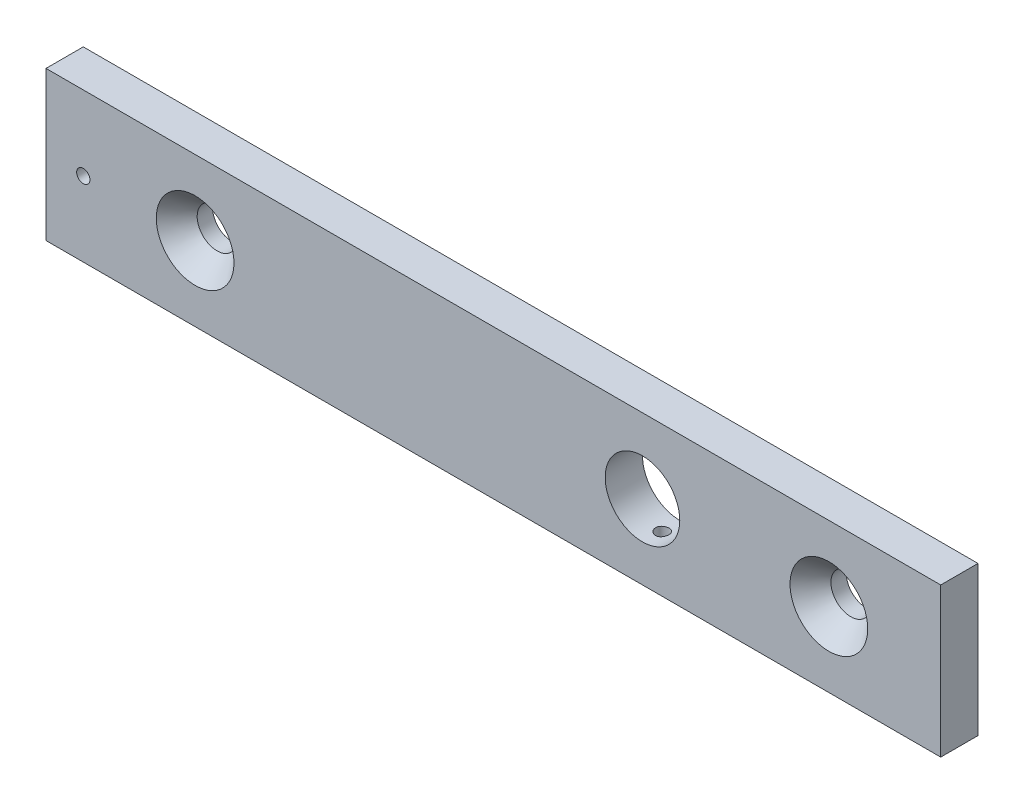
SolidWorks part; units mm, degrees
material "Brass"
ref_plane "Front Plane" through (0, 0, 0) normal (0, 0, 1) x (1, 0, 0)
ref_plane "Top Plane" through (0, 0, 0) normal (0, 1, 0) x (1, 0, 0)
ref_plane "Right Plane" through (0, 0, 0) normal (1, 0, 0) x (0, 0, -1)
sketch "Sketch1" plane through (0, 0, 0) normal (0, 0, 1) x (1, 0, 0)
  line L0 (-76.2, 12.7) -> (76.2, -12.7) construction
  line L1 (-76.2, 12.7) -> (76.2, 12.7)
  line L2 (-76.2, 12.7) -> (-76.2, -12.7)
  line L3 (-76.2, -12.7) -> (76.2, -12.7)
  line L4 (76.2, 12.7) -> (76.2, -12.7)
  dimension "D1" = 152.4
  dimension "D2" = 25.4
extrude "Extrude1" add sketch "Sketch1" along normal blind 6.35
hole_wizard "#4-40 Tapped Hole2" positions "3DSketch2" profile "Sketch10" tap size "#4-40" standard "Ansi Inch"
sketch3d "3DSketch2"
  line L0 (-76.2, 12.7, 6.35) -> (-76.2, -12.7, 6.35) construction
  line L1 (-76.2, -12.7, 6.35) -> (76.2, -12.7, 6.35) construction
  point P0 (-69.85, 0, 6.35)
  dimension "D1" = 6.35
  dimension "D2" = 12.7
sketch "Sketch10" plane through (-69.85, 0, 6.35) normal (1, 0, 0) x (0, -1, 0)
  line L0 (0, 0) -> (0, 3.9812)
  line L1 (0, 3.9812) -> (1.1303, 3.302)
  line L2 (1.1303, 3.302) -> (1.1303, 0)
  line L5 (1.1303, 0) -> (0, 0)
  line L10 (0, 3.9812) -> (-1.1303, 3.302) construction
  line L11 (0, -6.35) -> (0, 107.95) construction
  dimension "Tap Drill Dia." = 2.2606
  dimension "Tap Drill Depth" = 3.302
  dimension "Drill Angle" = 118
cosmetic thread "Hole Thread3" parameters "D1"=3.302, "D2"=2.8448
hole_wizard "1/2 (0.5) Diameter Hole1" positions "3DSketch3" profile "Sketch13" hole size "1/2" standard "Ansi Inch" end condition through all
sketch3d "3DSketch3"
  line L0 (76.2, 12.7, 6.35) -> (-76.2, 12.7, 6.35) construction
  line L1 (-76.2, 12.7, 6.35) -> (-76.2, -12.7, 6.35) construction
  point P0 (25.4, 0, 6.35)
  dimension "D1" = 12.7
  dimension "D2" = 101.6
sketch "Sketch13" plane through (25.4, 0, 6.35) normal (1, 0, 0) x (0, -1, 0)
  line L0 (0, 0) -> (0, 6.35)
  line L1 (0, 6.35) -> (6.35, 6.35)
  line L2 (6.35, 6.35) -> (6.35, 0)
  line L5 (6.35, 0) -> (0, 0)
  line L11 (0, -6.35) -> (0, 107.95) construction
  dimension "Thru Hole Dia." = 12.7
  dimension "Thru Hole Depth" = 6.35
hole_wizard "#4-40 Tapped Hole3" positions "3DSketch4" profile "Sketch14" tap size "#4-40" standard "Ansi Inch"
sketch3d "3DSketch4"
  point P0 (25.6107, -12.7, 3.1789)
sketch "Sketch14" plane through (25.6107, -12.7, 3.1789) normal (1, 0, 0) x (0, 0, -1)
  line L0 (0, 0) -> (0, 9.5692)
  line L1 (0, 9.5692) -> (1.1303, 8.89)
  line L2 (1.1303, 8.89) -> (1.1303, 0)
  line L5 (1.1303, 0) -> (0, 0)
  line L10 (0, 9.5692) -> (-1.1303, 8.89) construction
  line L11 (0, -6.35) -> (0, 107.95) construction
  dimension "Tap Drill Dia." = 2.2606
  dimension "Tap Drill Depth" = 8.89
  dimension "Drill Angle" = 118
cosmetic thread "Hole Thread4" parameters "D1"=5.588, "D2"=2.8448
hole_wizard "CSK for 1/4 Flat Head Socket Cap Screw3" positions "3DSketch5" profile "Sketch15" countersink size "1/4" standard "Ansi Inch"
sketch3d "3DSketch5"
  line L0 (76.2, 12.7, 6.35) -> (-76.2, 12.7, 6.35) construction
  line L1 (-76.2, 12.7, 6.35) -> (-76.2, -12.7, 6.35) construction
  point P0 (-50.8, 0, 6.35)
  point P2 (57.15, 0, 6.35)
  dimension "D1" = 12.7
  dimension "D2" = 12.7
  dimension "D3" = 25.4
  dimension "D4" = 133.35
sketch "Sketch15" plane through (-50.8, 0, 6.35) normal (1, 0, 0) x (0, -1, 0)
  line L0 (0, 0) -> (0, 11.5548)
  line L1 (0, 11.5548) -> (3.3782, 9.525)
  line L2 (3.3782, 9.525) -> (3.3782, 3.7284)
  line L3 (3.3782, 3.7284) -> (6.6192, 0)
  line L5 (6.6192, 0) -> (0, 0)
  line L6 (-3.3782, 3.7284) -> (-6.6192, 0) construction
  line L10 (0, 11.5548) -> (-3.3782, 9.525) construction
  line L11 (0, -6.35) -> (0, 107.95) construction
  dimension "Hole Dia." = 6.7564
  dimension "Hole Depth" = 9.525
  dimension "Near C'Sink Dia." = 13.2385
  dimension "Near C'Sink Angle" = 82
  dimension "Drill Angle" = 118
hole_wizard "CSK for 1/4 Flat Head Socket Cap Screw4" positions "Sketch16" profile "Sketch17" countersink size "1/4" standard "Ansi Inch" end condition through all
sketch "Sketch16" plane through (-2.2962, -5.3613, 6.35) normal (0, 0, 1) x (1, 0, 0)
  point P0 (-48.5038, 5.3613)
sketch "Sketch17" plane through (-50.8, 0, 6.35) normal (1, 0, 0) x (0, -1, 0)
  line L0 (0, 0) -> (0, 6.35)
  line L1 (0, 6.35) -> (3.3782, 6.35)
  line L2 (3.3782, 6.35) -> (3.3782, 3.7284)
  line L3 (3.3782, 3.7284) -> (6.6192, 0)
  line L5 (6.6192, 0) -> (0, 0)
  line L6 (-3.3782, 3.7284) -> (-6.6192, 0) construction
  line L11 (0, -6.35) -> (0, 107.95) construction
  dimension "Thru Hole Dia." = 6.7564
  dimension "Thru Hole Depth" = 6.35
  dimension "Near C'Sink Dia." = 13.2385
  dimension "Near C'Sink Angle" = 82
hole_wizard "CSK for 1/4 Flat Head Socket Cap Screw5" positions "Sketch18" profile "Sketch19" countersink size "1/4" standard "Ansi Inch" end condition through all
sketch "Sketch18" plane through (-2.2962, -5.3613, 6.35) normal (0, 0, 1) x (1, 0, 0)
  point P0 (59.4462, 5.3613)
sketch "Sketch19" plane through (57.15, 0, 6.35) normal (1, 0, 0) x (0, -1, 0)
  line L0 (0, 0) -> (0, 6.35)
  line L1 (0, 6.35) -> (3.3782, 6.35)
  line L2 (3.3782, 6.35) -> (3.3782, 3.7284)
  line L3 (3.3782, 3.7284) -> (6.6192, 0)
  line L5 (6.6192, 0) -> (0, 0)
  line L6 (-3.3782, 3.7284) -> (-6.6192, 0) construction
  line L11 (0, -6.35) -> (0, 107.95) construction
  dimension "Thru Hole Dia." = 6.7564
  dimension "Thru Hole Depth" = 6.35
  dimension "Near C'Sink Dia." = 13.2385
  dimension "Near C'Sink Angle" = 82
